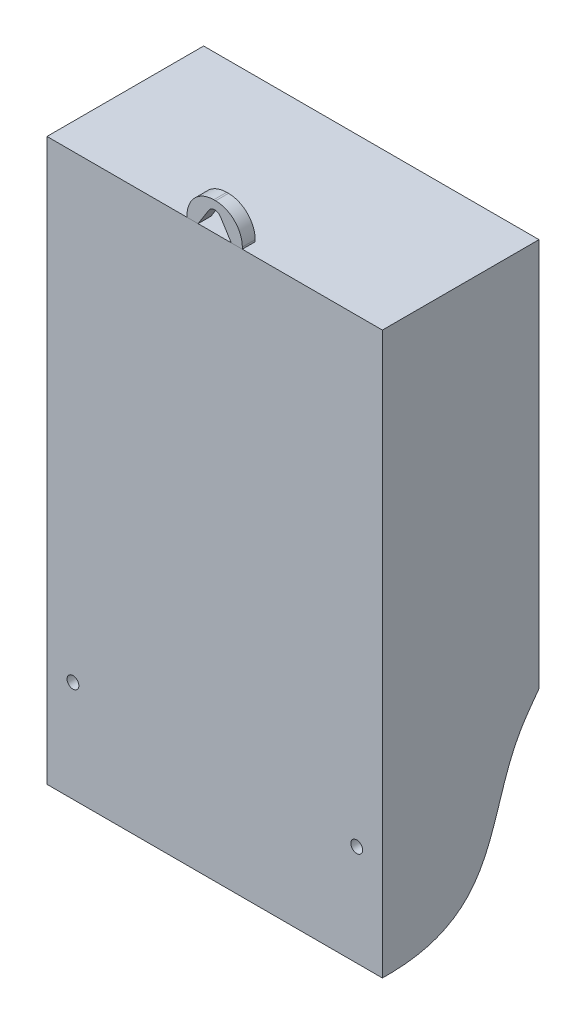
SolidWorks part; units mm, degrees
ref_plane "Спереди" through (0, 0, 0) normal (0, 0, 1) x (1, 0, 0)
ref_plane "Сверху" through (0, 0, 0) normal (0, 1, 0) x (1, 0, 0)
ref_plane "Справа" through (0, 0, 0) normal (1, 0, 0) x (0, 0, -1)
sketch "Эскиз1" plane through (0, 0, 0) normal (0, 0, 1) x (1, 0, 0)
  line L1 (91, -152.25) -> (-91, -152.25)
  line L2 (91, -152.25) -> (91, 152.25)
  line L3 (91, 152.25) -> (-91, 152.25)
  line L4 (-91, -152.25) -> (-91, 152.25)
  line L5 (91, -152.25) -> (-91, 152.25) construction
  line L6 (91, 152.25) -> (-91, -152.25) construction
  point P0 (0, 0)
  dimension "D1" = 304.5
  dimension "D2" = 182
extrude "Бобышка-Вытянуть1" add sketch "Эскиз1" along normal blind 85
sketch "Эскиз3" plane through (0, 0, 85) normal (0, 0, 1) x (1, 0, 0)
  line L0 (0, 152.25) -> (0, -152.25) construction
  line L1 (91, 152.25) -> (-91, 152.25) construction
  line L2 (-91, -152.25) -> (91, -152.25) construction
  line L5 (-9, 152.25) -> (-3.1728, 161.499)
  line L8 (0, 152.25) -> (0, 183.2938) construction
  line L9 (0.5, 167.75) -> (-0.5, 167.75)
  line L10 (-15, 153.25) -> (-15, 152.25)
  line L11 (91, 152.25) -> (-91, 152.25) construction
  line L12 (-91, -152.25) -> (91, -152.25) construction
  line L13 (15, 153.25) -> (15, 152.25)
  line L14 (-15, 152.25) -> (-9, 152.25)
  line L15 (9, 152.25) -> (3.1728, 161.499)
  line L16 (15, 152.25) -> (9, 152.25)
  arc A1 (-15, 153.25) -> (-0.5, 167.75) centre (-0.5, 153.25) cw
  arc A3 (15, 153.25) -> (0.5, 167.75) centre (0.5, 153.25) ccw
  arc A4 (3.1728, 161.499) -> (-3.1728, 161.499) centre (0, 159.5) ccw
  point P17 (-15, 167.75)
  point P19 (0, 167.75)
  dimension "D3" = 14.5
  dimension "D4" = 8.25
  dimension "D1" = 320
  dimension "D2" = 15
  dimension "D6" = 7.5
  dimension "D5" = 6
extrude "Бобышка-Вытянуть2" add sketch "Эскиз3" against normal blind 7 separate body
sketch "Эскиз4" plane through (91, 0, 0) normal (1, 0, 0) x (0, 0, -1)
  line L0 (0, -152.25) -> (0, 152.25) construction
  line L1 (-85, 152.25) -> (0, 152.25) construction
  line L2 (-85, -152.25) -> (-85, 152.25) construction
  spline S0 degree 3 poles (-85, -152.25) (-21.2984, -153.5828) (-30.3152, -98.8701) (-3.645, -63.8106) (0, -58.75) knots 0 0 0 0 0.856672 1 1 1 1
  line M1 (0, -152.25) -> (0, 152.25)
  line M4 (-85, -152.25) -> (0, -152.25)
  dimension "D1" = 211
  dimension "D2" = 61
extrude "Вырез-Вытянуть1" cut sketch "Эскиз4" against normal through all and the other way through all contours S0 M4 M1
sketch "Эскиз5" plane through (0, 0, 85) normal (0, 0, 1) x (1, 0, 0)
  line L0 (0, -152.25) -> (0.5, 167.75) construction
  line L1 (-91, -152.25) -> (91, -152.25) construction
  circle A0 centre (0, 159.5) radius 3.75
  arc A1 (3.1728, 161.499) -> (-3.1728, 161.499) centre (0, 159.5) ccw construction
  circle A2 centre (77.0856, -97.5) radius 3.2
  circle A3 centre (-76.9142, -97.2594) radius 3.2
  dimension "D1" = 7.5
  dimension "D2" = 6.4
  dimension "D3" = 77
  dimension "D4" = 257
extrude "Вырез-Вытянуть2" cut sketch "Эскиз5" against normal blind 5
sketch "Эскиз6" plane through (0, 0, 0) normal (0, 0, -1) x (-1, 0, 0)
  line L1 (81.0826, 29.3414) -> (-81.0826, 29.3414)
  line L2 (81.0826, 29.3414) -> (81.0826, 121.2197)
  line L3 (81.0826, 121.2197) -> (-81.0826, 121.2197)
  line L4 (-81.0826, 29.3414) -> (-81.0826, 121.2197)
  line L5 (81.0826, 29.3414) -> (-81.0826, 121.2197) construction
  line L6 (81.0826, 121.2197) -> (-81.0826, 29.3414) construction
  point P0 (0, 75.2806)
extrude "Вырез-Вытянуть3" cut sketch "Эскиз6" against normal blind 0.1
